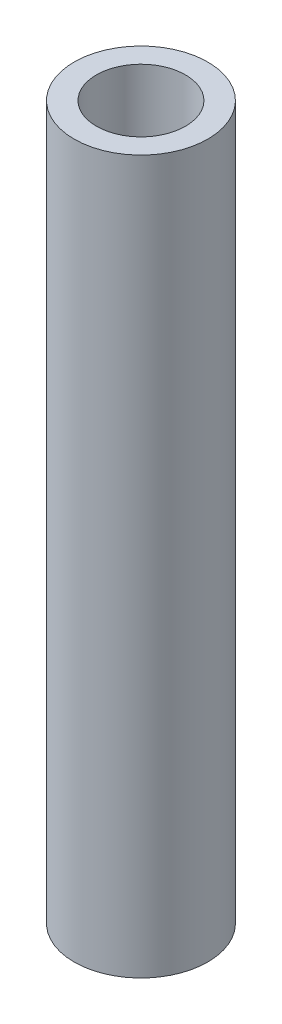
SolidWorks part; units mm, degrees
material "NEOPRENE"
ref_plane "Front" through (0, 0, 0) normal (0, 0, 1) x (1, 0, 0)
ref_plane "Top" through (0, 0, 0) normal (0, 1, 0) x (1, 0, 0)
ref_plane "Right" through (0, 0, 0) normal (1, 0, 0) x (0, 0, -1)
sketch "Sketch1" plane through (0, 0, 0) normal (0, 1, 0) x (1, 0, 0)
  circle A0 centre (0, 0) radius 6.35
  circle A1 centre (0, 0) radius 9.525
  dimension "D1" = 19.05
  dimension "D2" = 12.7
extrude "Boss-Extrude1" add sketch "Sketch1" along normal blind 101.6
